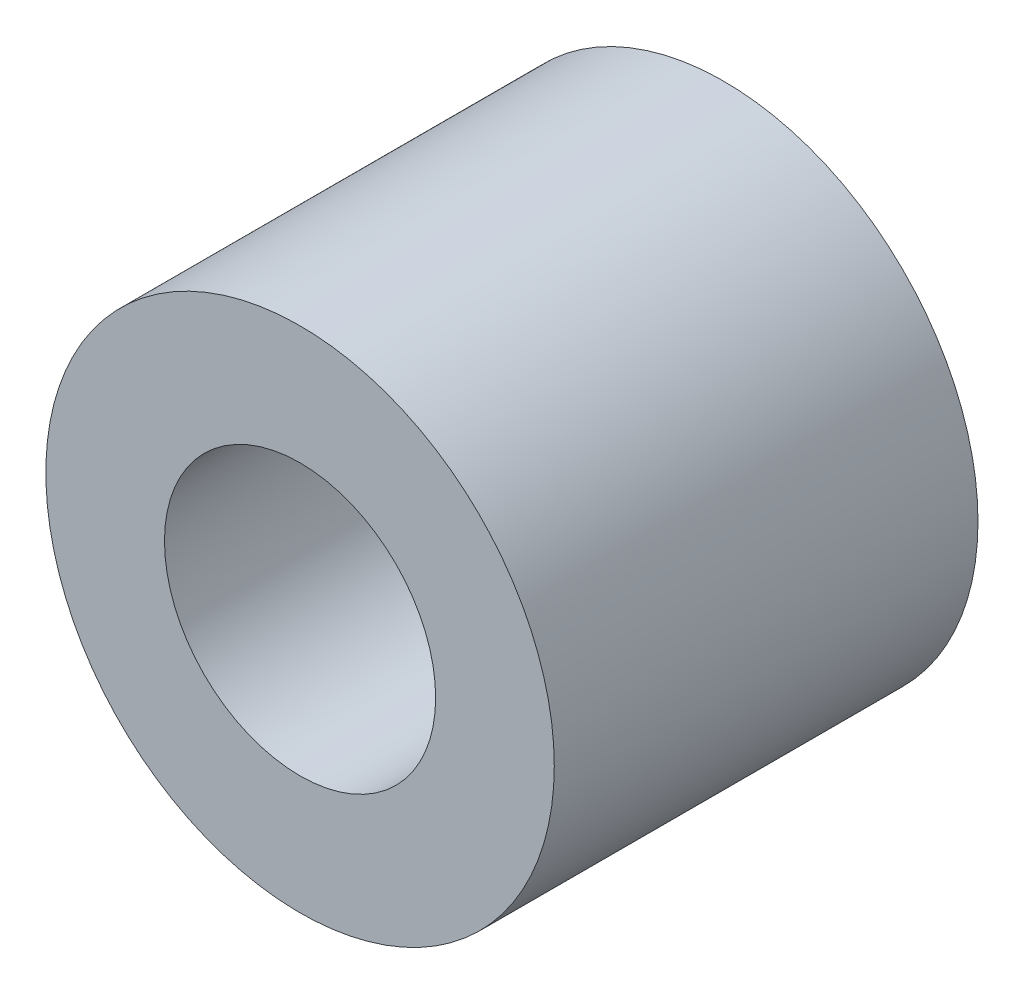
SolidWorks part; units mm, degrees
ref_plane "Front Plane" through (0, 0, 0) normal (0, 0, 1) x (1, 0, 0)
ref_plane "Top Plane" through (0, 0, 0) normal (0, 1, 0) x (1, 0, 0)
ref_plane "Right Plane" through (0, 0, 0) normal (1, 0, 0) x (0, 0, -1)
sketch "Sketch1" plane through (0, 0, 0) normal (0, 0, 1) x (1, 0, 0)
  line L3 (0, 0) -> (0, 3) construction
  circle A0 centre (0, 0) radius 1.6
  circle A1 centre (0, 0) radius 3
  dimension "D1" = 3.2
  dimension "D2" = 6
extrude "Boss-Extrude1" add sketch "Sketch1" along normal blind 5
